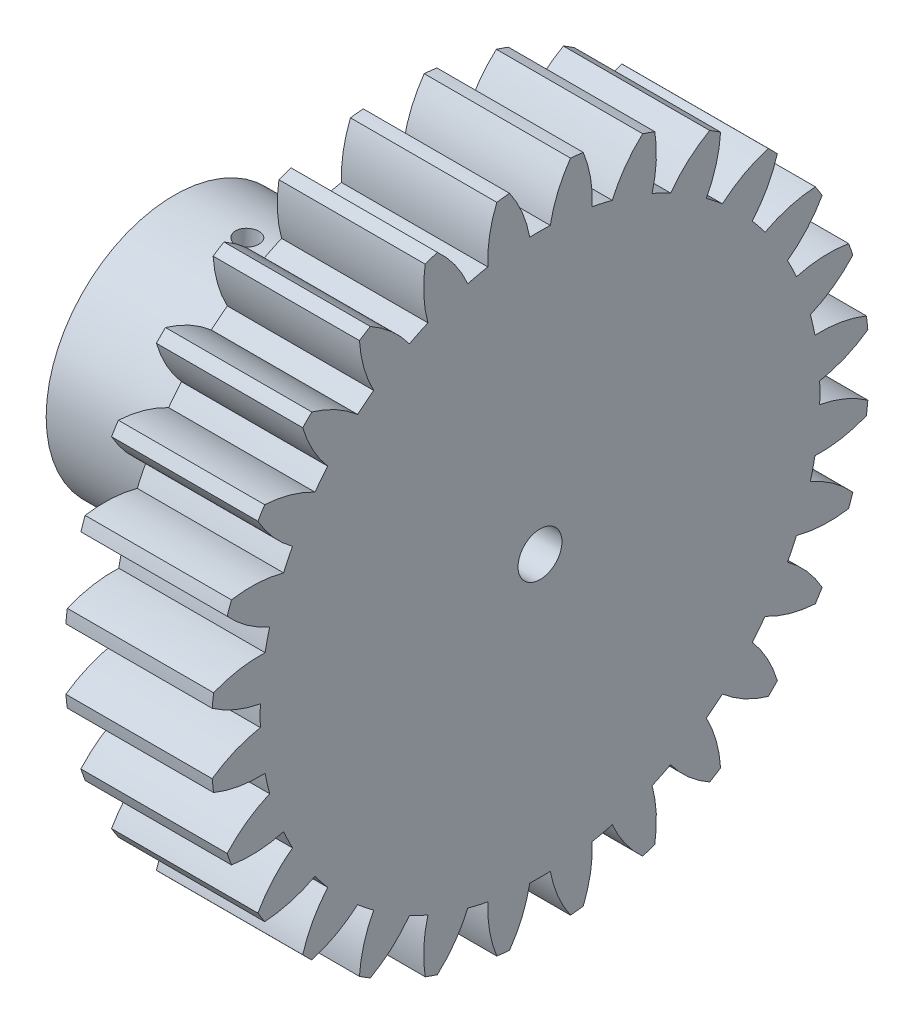
SolidWorks part; units mm, degrees
ref_plane "Plane1" through (0, 0, 0) normal (0, 0, 1) x (1, 0, 0)
ref_plane "Plane2" through (0, 0, 0) normal (0, 1, 0) x (1, 0, 0)
ref_plane "Plane3" through (0, 0, 0) normal (1, 0, 0) x (0, 0, -1)
sketch "HoldingSke" plane through (0, 0, 0) normal (0, 1, 0) x (1, 0, 0)
  line L0 (0, 0) -> (0.2943, -0.1565)
  line L1 (-15, 0) -> (100, 0) construction
  line L2 (0, 0) -> (-2.1039, 2.3779)
  line L3 (0, 0) -> (-11.863, 4.5341)
  line L4 (0, 0) -> (7.6251, 4.0544)
  line L5 (0, 0) -> (-46.8476, -17.4728)
  line L6 (0, 0) -> (-16.5793, -11.1861)
  line L7 (-2.1039, 2.3779) -> (8.6586, 51.2059)
  line L8 (-76.2, 54.61) -> (-75.2, 54.61)
  line L9 (-71.009, 38.7566) -> (-53.1078, 45.2721)
  line L10 (-76.2, 71.12) -> (104.1128, 71.12)
  line L11 (0, 0) -> (-20, 0)
  line L12 (-76.2, 101.6) -> (-76.093, 101.6)
  line L13 (24.9733, 27.94) -> (52.9518, 28.4284)
  line L14 (24.9733, 27.94) -> (24.9743, 27.94)
  line L15 (24.9733, 27.94) -> (100.4006, 29.5858)
  line L16 (-63.627, -3) -> (-12.827, -3)
  circle A0 centre (0, 0) radius 3
  circle A1 centre (0, 0) radius 17.5
  circle A2 centre (0, 0) radius 17.5
  circle A3 centre (0, 0) radius 3
  dimension "MHD" = 35
  dimension "Hub_dia" = 35
  dimension "Bore" = 6
  dimension "MBD" = 6
  dimension "Num_teeth" = 28
  dimension "Pitch" = 0.3333
  dimension "Overall_len" = 50
  dimension "Show_teeth" = 28
  dimension "Thickness" = 20
  dimension "OAL" = 50.0001
  dimension "T_dim" = 1
  dimension "Ap" = 20
  dimension "H" = 19.05
  dimension "Pitch_radius" = 180.3128
  dimension "Width" = 20
  dimension "Backlash" = 0.107
  dimension "Addendum_fac" = 1
  dimension "Dedendum_fac" = 1.25
  dimension "Clearance_fac" = 0.25
  dimension "Dedendum_add" = 0.001
  dimension "Module" = 3
sketch "BasProSke" plane through (0, 0, 0) normal (0, 1, 0) x (1, 0, 0)
  line L0 (-10, 0) -> (60, 0) construction
  line L1 (0, 0) -> (0, 45)
  line L2 (0, 0) -> (20, 0)
  line L3 (20, 0) -> (20, 45)
  line L4 (20, 45) -> (0, 45)
  dimension "Thickness" = 20
  dimension "Diameter" = 90
revolve "Base-Revolve" add sketch "BasProSke" angle 360 about L0
sketch "TooCutSke" plane through (0, 0, 0) normal (1, 0, 0) x (0, 0, -1)
  line L1 (0, 0) -> (0, 107) construction
  line L2 (0, 0) -> (-2.5422, 41.923) construction
  line L3 (0, 0) -> (-9.3925, 83.3606) construction
  line L4 (-2.5422, 41.923) -> (-4.6962, 41.6803) construction
  arc A0 (1.4032, 38.2233) -> (-1.4032, 38.2233) centre (0, 0) ccw
  arc A1 (4.1825, 44.8307) -> (-4.1825, 44.8307) centre (0, 0) ccw
  circle A2 centre (0, 0) radius 42 construction
  circle A3 centre (0, 0) radius 39.4671 construction
  arc A4 (-1.4032, 38.2233) -> (-4.1825, 44.8307) centre (-17.9222, 35.1632) ccw
  arc A5 (4.1825, 44.8307) -> (1.4032, 38.2233) centre (17.9222, 35.1632) ccw
  dimension "Root_dia" = 76.498
  dimension "Overcut_dia" = 90.0508
  dimension "Pitch_dia" = 84
  dimension "Base_dia" = 78.9342
  dimension "Flank_rad" = 16.8
  dimension "Half_ang" = 6.429
  dimension "Half_CT" = 2.1677
extrude "ToothCut" cut sketch "TooCutSke" along normal through all
fillet "Breaks" [suppressed] radius 0.06
fillet "RootFillets" [suppressed] radius 0.751
pattern_circular "TeethCuts" count 28 every 12.857 about axis through (-10, 0, 0) along (1, 0, 0) of "ToothCut", "RootFillets", "Breaks"
sketch "HubNeaOneSke" plane through (0, 0, 0) normal (-1, 0, 0) x (0, 0, 1)
  circle A0 centre (0, 0) radius 17.5
  dimension "Diameter" = 35
extrude "HubNearOne" add sketch "HubNeaOneSke" along normal blind 30.0001
sketch "HubNeaBotSke" plane through (0, 0, 0) normal (-1, 0, 0) x (0, 0, 1)
  circle A0 centre (0, 0) radius 17.5
  dimension "Diameter" = 35
extrude "HubNearBoth" [suppressed] add sketch "HubNeaBotSke" along normal blind 15
ref_plane "FarPln" through (20, 0, 0) normal (1, 0, 0) x (0, 0, -1)
sketch "HubFarSke" plane through (20, 0, 0) normal (1, 0, 0) x (0, 0, -1)
  circle A0 centre (0, 0) radius 17.5
  dimension "Diameter" = 35
extrude "HubFar" [suppressed] add sketch "HubFarSke" along normal blind 15
sketch "BorSke" plane through (0, 0, 0) normal (1, 0, 0) x (0, 0, -1)
  circle A0 centre (0, 0) radius 3
  dimension "Diameter" = 6
extrude "Bore" cut sketch "BorSke" along normal mid plane 100.0001
sketch "KeySke" plane through (0, 0, 0) normal (1, 0, 0) x (0, 0, -1)
  line L0 (-1, 0) -> (-1, 4)
  line L1 (-1, 4) -> (1, 4)
  line L2 (1, 4) -> (1, 0)
  line L3 (0, 0) -> (0, 34) construction
  line L4 (-1, 0) -> (1, 0)
  dimension "Offset" = 4
extrude "Keyway" [suppressed] cut sketch "KeySke" along normal mid plane 100.0001
pattern_circular "Keyway2" [suppressed] count 2 every 90 about axis through (-10, 0, 0) along (1, 0, 0)
sketch "Croquis1" plane through (0, 0, 0) normal (0, 1, 0) x (1, 0, 0)
  line L0 (33.124, 0) -> (-57.5849, 0) construction
  line L1 (-30.0001, 17.5) -> (-30.0001, -17.5) construction
  circle A0 centre (-12.0001, 0) radius 1.59
  circle A1 centre (-20.0001, 0) radius 1.59
  dimension "D1" = 3.18
  dimension "D2" = 8
  dimension "D3" = 10
extrude "Cortar-Extruir1" cut sketch "Croquis1" against normal mid plane 50
sketch "Croquis2" plane through (-30.0001, 0, 0) normal (-1, 0, 0) x (0, 0, 1)
  line L0 (0, 10.5) -> (0, -10.5) construction
  line L1 (-3, 10.5) -> (3, 10.5)
  line L2 (-3, 10.5) -> (-3, 7)
  line L3 (-3, 7) -> (3, 7)
  line L4 (3, 10.5) -> (3, 7)
  line L5 (-3, -7) -> (3, -7)
  line L6 (-3, -7) -> (-3, -10.5)
  line L7 (-3, -10.5) -> (3, -10.5)
  line L8 (3, -7) -> (3, -10.5)
  line L9 (13.7372, 0) -> (-13.7555, 0) construction
  dimension "D1" = 3.5
  dimension "D2" = 3.5
  dimension "D3" = 6
  dimension "D4" = 7
extrude "Cortar-Extruir2" cut sketch "Croquis2" against normal blind 26
equation "' \"Module@HoldingSke\" = 6.35"
equation "' \"Num_teeth@HoldingSke\" = 12"
equation "' \"Ap@HoldingSke\" =  20"
equation "' \"Ap@HoldingSke\" = 20"
equation "' \"Width@HoldingSke\" = 0.5 * 25.4"
equation "' \"Hub_dia@HoldingSke\"= 1 * 25.4"
equation "' \"Hub_dia@HoldingSke\" = 1 * 25.4"
equation "' \"Overall_len@HoldingSke\" = 1.0 * 25.4"
equation "' \"Bore@HoldingSke\" = 0.75 * 25.4"
equation "' \"T_dim@HoldingSke\" = 0.1 * 25.4"
equation "' \"Width@KeySke\" = 0.25 * 25.4"
equation "' \"Show_teeth@HoldingSke\" = 13"
equation "' \"Backlash@HoldingSke\" = 0.009 * 25.4"
equation "' \"Addendum_fac@HoldingSke\" = 1.0"
equation "' \"Dedendum_fac@HoldingSke\" = 1.25"
equation "' \"Dedendum_add@HoldingSke\" = 0.00005 * 25.4"
equation "' \"Clearance_fac@HoldingSke\" = 0.25"
equation "\"Pitch@HoldingSke\" = 1 / \"Module@HoldingSke\""
equation "\"Overcut_dia@TooCutSke\" = (\"Num_teeth@HoldingSke\" + 2 * \"Addendum_fac@HoldingSke\") / \"Pitch@HoldingSke\" + 0.002 * 25.4"
equation "\"Pitch_dia@TooCutSke\" = \"Num_teeth@HoldingSke\" / \"Pitch@HoldingSke\""
equation "\"Base_dia@TooCutSke\" = \"Num_teeth@HoldingSke\" / \"Pitch@HoldingSke\" * cos((\"Ap@HoldingSke\"  * 3.14159265 / 180))"
equation "\"Root_dia@TooCutSke\" = (\"Num_teeth@HoldingSke\" + 2) / \"Pitch@HoldingSke\" - 2 * (\"Addendum_fac@HoldingSke\" + \"Dedendum_fac@HoldingSke\") / \"Pitch@HoldingSke\" - \"Dedendum_add@HoldingSke\" * 2"
equation "\"Half_ang@TooCutSke\" = 180 / \"Num_teeth@HoldingSke\""
equation "\"Half_CT@TooCutSke\" = \"Num_teeth@HoldingSke\" / \"Pitch@HoldingSke\" * sin((3.14159265 / 2 / \"Num_teeth@HoldingSke\")) / 2 - 7 * \"Backlash@HoldingSke\" / 4"
equation "\"Flank_rad@TooCutSke\" = \"Num_teeth@HoldingSke\" / \"Pitch@HoldingSke\" / 5"
equation "\"Radius@RootFillets\" = \"Clearance_fac@HoldingSke\" / \"Pitch@HoldingSke\" + \"Dedendum_add@HoldingSke\""
equation "\"Break_rad@Breaks\" = 0.02 / \"Pitch@HoldingSke\""
equation "\"Thickness@HoldingSke\" = \"Width@HoldingSke\""
equation "\"OAL@HoldingSke\" = \"Thickness@HoldingSke\""
equation "\"MHD@HoldingSke\" = (\"Num_teeth@HoldingSke\" + 2) / \"Pitch@HoldingSke\" - 2 * (\"Addendum_fac@HoldingSke\" + \"Dedendum_fac@HoldingSke\")  / \"Pitch@HoldingSke\" - \"Dedendum_add@HoldingSke\" * 2"
equation "\"MBD@HoldingSke\" = (\"Num_teeth@HoldingSke\" + 2) / \"Pitch@HoldingSke\" - 2 * (\"Addendum_fac@HoldingSke\" + \"Dedendum_fac@HoldingSke\")  / \"Pitch@HoldingSke\" - \"Dedendum_add@HoldingSke\" * 2 - 0.002 * 25.4"
equation "\"MHD@HoldingSke\" = ((sgn( \"MHD@HoldingSke\" - \"Hub_dia@HoldingSke\" )-1)*( \"MHD@HoldingSke\" - \"Hub_dia@HoldingSke\" ))/-2+ \"Hub_dia@HoldingSke\""
equation "\"MBD@HoldingSke\" = ((sgn( \"MBD@HoldingSke\" - \"Bore@HoldingSke\" )-1)*( \"MBD@HoldingSke\" - \"Bore@HoldingSke\" ))/-2+ \"Bore@HoldingSke\""
equation "\"OAL@HoldingSke\" = ((sgn( \"OAL@HoldingSke\" - \"Overall_len@HoldingSke\" )+1)*( \"OAL@HoldingSke\" - \"Overall_len@HoldingSke\" ))/2 + \"Overall_len@HoldingSke\" + 0.000002 * 25.4"
equation "\"Num_teeth@TeethCuts\" = int( \"Show_teeth@HoldingSke\" ) + 1"
equation "\"Num_teeth@TeethCuts\" = ((sgn( \"Num_teeth@TeethCuts\" - \"Num_teeth@HoldingSke\" )-1)*( \"Num_teeth@TeethCuts\" - \"Num_teeth@HoldingSke\" ))/-2+ \"Num_teeth@HoldingSke\""
equation "\"Num_teeth@TeethCuts\" = ((sgn( \"Num_teeth@TeethCuts\" - 2.0)+1)*( \"Num_teeth@TeethCuts\" - 2.0))/2 +2.0"
equation "\"Angle@TeethCuts\" = 360.0 / \"Num_teeth@HoldingSke\""
equation "\"Diameter@BasProSke\" = (\"Num_teeth@HoldingSke\" + 2 * \"Addendum_fac@HoldingSke\") / \"Pitch@HoldingSke\""
equation "\"Thickness@BasProSke\"  = \"Thickness@HoldingSke\""
equation "' \"Fillet_rad@BasProSke\" =  \"Thickness@HoldingSke\" * 0.05"
equation "' \"Fillet_rad@BasProSke\" = \"Thickness@HoldingSke\" * 0.05"
equation "\"MHD@HoldingSke\" = ((sgn( \"MHD@HoldingSke\" - \"Root_dia@TooCutSke\" )-1)*( \"MHD@HoldingSke\" - \"Root_dia@TooCutSke\" ))/-2+ \"Root_dia@TooCutSke\""
equation "\"Diameter@HubNeaOneSke\" = \"MHD@HoldingSke\""
equation "\"Length@HubNearOne\" = \"OAL@HoldingSke\" - \"Thickness@BasProSke\""
equation "\"Diameter@HubNeaBotSke\" = \"MHD@HoldingSke\""
equation "\"Length@HubNearBoth\" = ( \"OAL@HoldingSke\" - \"Thickness@BasProSke\" ) / 2.0"
equation "\"Thickness@FarPln\" = \"Thickness@BasProSke\""
equation "\"Diameter@HubFarSke\" = \"MHD@HoldingSke\""
equation "\"Length@HubFar\" = ( \"OAL@HoldingSke\" - \"Thickness@BasProSke\" ) / 2.0"
equation "\"Diameter@BorSke\" = \"MBD@HoldingSke\""
equation "\"D1@Bore\" = \"OAL@HoldingSke\" * 2.0"
equation "\"D1@Keyway\" = \"OAL@HoldingSke\" * 2.0"
equation "\"Offset@KeySke\" = \"T_dim@HoldingSke\" + \"MBD@HoldingSke\" / 2.0"
